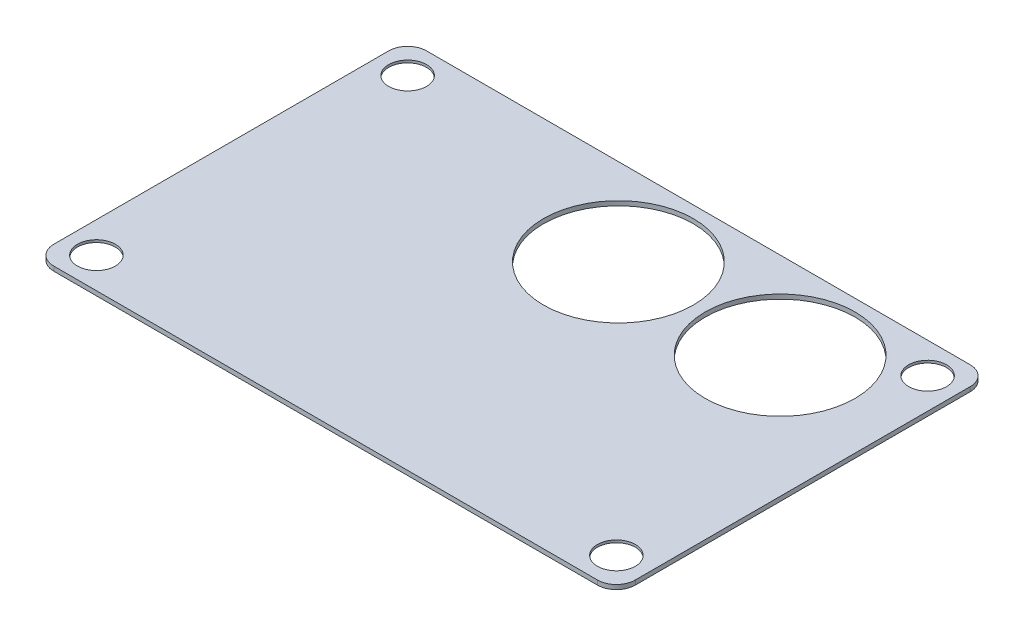
SolidWorks part; units mm, degrees
ref_plane "Front Plane" through (0, 0, 0) normal (0, 0, 1) x (1, 0, 0)
ref_plane "Top Plane" through (0, 0, 0) normal (0, 1, 0) x (1, 0, 0)
ref_plane "Right Plane" through (0, 0, 0) normal (1, 0, 0) x (0, 0, -1)
sketch "Sketch1" plane through (0, 0, 0) normal (0, 1, 0) x (1, 0, 0)
  line L1 (0, 0) -> (78, 0)
  line L2 (0, 0) -> (0, 50)
  line L3 (0, 50) -> (78, 50)
  line L4 (78, 0) -> (78, 50)
  dimension "D1" = 78
  dimension "D2" = 50
extrude "pcb" add sketch "Sketch1" along normal blind 0.6
fillet "card edges" radius 2.54 4 edges at (78, 0.3, -50) (0, 0.3, -50) (0, 0.3, 0) (78, 0.3, 0)
sketch "Sketch4" plane through (0, 0.6, 0) normal (0, 1, 0) x (1, 0, 0)
  line L11 (0, 47.46) -> (0, 2.54) construction
  line L13 (2.54, 0) -> (75.46, 0) construction
  circle A0 centre (4.1275, 4.13) radius 2.54
  dimension "D1" = 5.08
  dimension "D2" = 1.5875
  dimension "D3" = 1.59
extrude "magnet hole cut" cut sketch "Sketch4" against normal through all
sketch "Sketch8" plane through (0, 0, 0) normal (0, -1, 0) x (1, 0, 0)
  circle A0 centre (4.1275, -4.13) radius 3.33
  circle A1 centre (4.1275, -4.13) radius 2.54 construction
  dimension "D1" = 0.79
extrude "steel inlay cut" cut sketch "Sketch8" against normal blind 0.2666
ref_plane "Plane1" through (39, 0, 0) normal (1, 0, 0) x (0, 0, -1)
ref_plane "Plane2" through (0, 0, -25) normal (0, 0, 1) x (1, 0, 0)
mirror "Mirror1" about plane through (0, 0, -25) normal (0, 0, 1) of "steel inlay cut", "magnet hole cut"
mirror "Mirror2" about plane through (39, 0, 0) normal (1, 0, 0) of "Mirror1", "magnet hole cut", "steel inlay cut"
sketch "Sketch15" plane through (0, 0.6, 0) normal (0, 1, 0) x (1, 0, 0)
  line L3 (75.46, 50) -> (2.54, 50) construction
  line L4 (78, 2.54) -> (78, 47.46) construction
  circle A0 centre (61.6, 38.3625) radius 10.05
  circle A1 centre (39.9125, 38.3625) radius 10.05
  dimension "D2" = 1.5875
  dimension "D1" = 20.1
  dimension "D4" = 1.5875
  dimension "D3" = 6.35
extrude "battery_holes" cut sketch "Sketch15" against normal through all
equation "\"magnet_inset\"= 0.0625in"
equation "\"magnet_diameter\"= 0.2in"
equation "\"D1@Sketch4\"=\"magnet_diameter\""
equation "\"steel_inset_distance\"= 1in / 32"
equation "\"D1@steel inlay cut\"= \"pcb_thickness\" - ( ( \"magnet_thickness\" / 2 ) - ( \"kapton_thickness\" / 2 ) )"
equation "\"kapton_thickness\"= 0.005in"
equation "\"pcb_thickness\"= 0.6mm"
equation "\"magnet_thickness\"= 0.03125in"
equation "\"D2@Sketch4\"=\"magnet_inset\""
equation "\"edge_radius\"= 1in / 10"
equation "\"card_width\"= 78mm"
equation "\"card_height\"= 50mm"
equation "\"battery_diameter\"= 20mm"
equation "\"battery_oversize\"= 0.1mm"
equation "\"battery_vertical_inset\"= 1in / 16"
equation "\"battery_horizontal_inset\"= 1in / 4"
equation "\"battery_spacing\"= 1in / 16"
equation "\"D1@Sketch15\"=\"battery_diameter\"+\"battery_oversize\""
equation "\"D4@Sketch15\"=\"battery_spacing\""
equation "\"D2@Sketch15\"=\"battery_vertical_inset\""
equation "\"D3@Sketch15\"=\"battery_horizontal_inset\""
equation "\"D2@Sketch1\"=\"card_height\""
equation "\"D1@Sketch1\"=\"card_width\""
equation "\"D1@Plane1\"=\"card_width\"/2"
equation "\"D1@Plane2\"=\"card_height\"/2"
